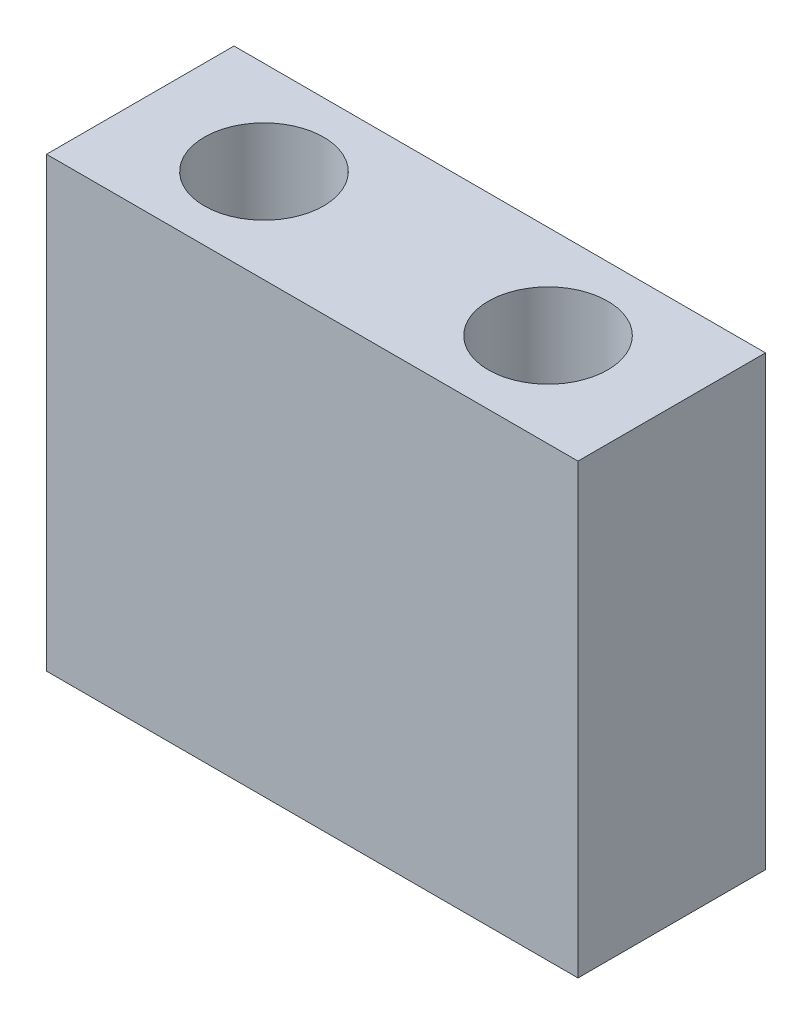
SolidWorks part; units mm, degrees
ref_plane "Front Plane" through (0, 0, 0) normal (0, 0, 1) x (1, 0, 0)
ref_plane "Top Plane" through (0, 0, 0) normal (0, 1, 0) x (1, 0, 0)
ref_plane "Right Plane" through (0, 0, 0) normal (1, 0, 0) x (0, 0, -1)
sketch "Sketch1" plane through (0, 0, 0) normal (0, 1, 0) x (1, 0, 0)
  line L1 (-9.355, 3.3) -> (9.355, 3.3)
  line L2 (-9.355, 3.3) -> (-9.355, -3.3)
  line L3 (-9.355, -3.3) -> (9.355, -3.3)
  line L4 (9.355, 3.3) -> (9.355, -3.3)
  line L5 (-9.355, 3.3) -> (9.355, -3.3) construction
  line L6 (-9.355, -3.3) -> (9.355, 3.3) construction
  point P0 (0, 0)
  dimension "D1" = 18.71
  dimension "D2" = 6.6
extrude "Boss-Extrude1" add sketch "Sketch1" along normal blind 15.76
hole_wizard "M5x0.8 Tapped Hole1" positions "Sketch5" profile "Sketch6" tap size "M5x0.8" standard "ANSI Metric" end condition through all
sketch "Sketch5" plane through (0, 15.76, 0) normal (0, 1, 0) x (1, 0, 0)
  point P0 (5, 0)
  point P2 (-5, 0)
  point P10 (5.6599, -4.8244)
  point P13 (0, 0)
  point P14 (0, 0)
  dimension "D1" = 5
  dimension "D2" = 5
cosmetic thread "Hole Thread1" parameters "D2"=5
cosmetic thread "Hole Thread2" parameters "D2"=5
sketch "Sketch6" plane through (5, 15.76, 0) normal (1, 0, 0) x (0, 0, 1)
  line L0 (0, 0) -> (0, 15.76)
  line L1 (0, 15.76) -> (2.1, 15.76)
  line L2 (2.1, 15.76) -> (2.1, 0)
  line L5 (2.1, 0) -> (0, 0)
  line L11 (0, -6.35) -> (0, 107.95) construction
  dimension "Thru Tap Drill Dia." = 4.2
  dimension "Thru Tap Drill Depth" = 15.76
